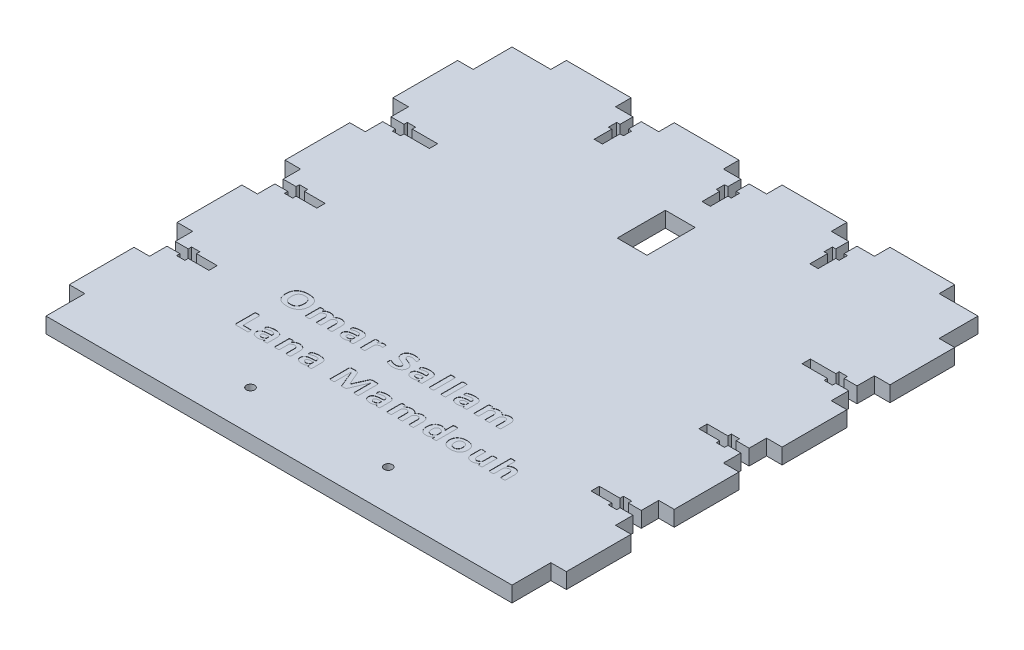
SolidWorks part; units mm, degrees
material "Oak"
ref_plane "Front Plane" through (0, 0, 0) normal (0, 0, 1) x (1, 0, 0)
ref_plane "Top Plane" through (0, 0, 0) normal (0, 1, 0) x (1, 0, 0)
ref_plane "Right Plane" through (0, 0, 0) normal (1, 0, 0) x (0, 0, -1)
sketch "Sketch1" plane through (0, 0, 0) normal (0, 1, 0) x (1, 0, 0)
  line L0 (0, -90) -> (0, 90) construction
  line L2 (90, 43.2667) -> (85, 43.2667)
  line L3 (90, 43.2667) -> (90, 40.0667)
  line L4 (90, 40.0667) -> (85, 40.0667)
  line L5 (72, 43.2667) -> (72, 40.0667)
  line L6 (81.8, 40.0667) -> (72, 40.0667)
  line L7 (81.8, 44.5667) -> (85, 44.5667)
  line L8 (81.8, 44.5667) -> (81.8, 43.2667)
  line L9 (81.8, 38.7667) -> (85, 38.7667)
  line L10 (85, 44.5667) -> (85, 43.2667)
  line L11 (81.8, 40.0667) -> (81.8, 38.7667)
  line L12 (81.8, 43.2667) -> (72, 43.2667)
  line L13 (85, 40.0667) -> (85, 38.7667)
  line L14 (90, 43.2667) -> (90, 50) construction
  line L15 (90, 40.0667) -> (90, 33.3333) construction
  line L16 (-85, 40.0667) -> (-85, 38.7667)
  line L17 (-81.8, 43.2667) -> (-72, 43.2667)
  line L18 (-81.8, 40.0667) -> (-81.8, 38.7667)
  line L19 (-85, 44.5667) -> (-85, 43.2667)
  line L20 (-81.8, 38.7667) -> (-85, 38.7667)
  line L21 (-81.8, 44.5667) -> (-81.8, 43.2667)
  line L22 (-81.8, 44.5667) -> (-85, 44.5667)
  line L23 (-81.8, 40.0667) -> (-72, 40.0667)
  line L24 (-72, 43.2667) -> (-72, 40.0667)
  line L25 (-90, 40.0667) -> (-85, 40.0667)
  line L26 (-90, 43.2667) -> (-90, 40.0667)
  line L27 (-90, 43.2667) -> (-85, 43.2667)
  line L34 (-5.75, 65) -> (5.75, 65)
  line L42 (-5.75, 65) -> (-5.75, 46.4)
  line L52 (-5.75, 46.4) -> (5.75, 46.4)
  line L53 (5.75, 65) -> (5.75, 46.4)
  circle A1 centre (26.6, -74.4) radius 1.6
  circle A2 centre (-26.6, -74.4) radius 1.6
  point P33 (0, 46.4)
  point P38 (25, -74.4)
  point P39 (26.6, -76)
  line B0 (90, 90) -> (75, 90)
  line B1 (75, 90) -> (75, 96)
  line B2 (75, 96) -> (50, 96)
  line B3 (50, 96) -> (50, 90)
  line B4 (50, 90) -> (43.2667, 90)
  line B5 (43.2667, 90) -> (43.2667, 85)
  line B6 (43.2667, 85) -> (44.5667, 85)
  line B7 (44.5667, 85) -> (44.5667, 81.8)
  line B8 (44.5667, 81.8) -> (43.2667, 81.8)
  line B9 (43.2667, 81.8) -> (43.2667, 75)
  line B10 (43.2667, 75) -> (40.0667, 75)
  line B11 (40.0667, 75) -> (40.0667, 81.8)
  line B12 (40.0667, 81.8) -> (38.7667, 81.8)
  line B13 (38.7667, 81.8) -> (38.7667, 85)
  line B14 (38.7667, 85) -> (40.0667, 85)
  line B15 (40.0667, 85) -> (40.0667, 90)
  line B16 (40.0667, 90) -> (33.3333, 90)
  line B17 (33.3333, 90) -> (33.3333, 96)
  line B18 (33.3333, 96) -> (8.3333, 96)
  line B19 (8.3333, 96) -> (8.3333, 90)
  line B20 (8.3333, 90) -> (1.6, 90)
  line B21 (1.6, 90) -> (1.6, 85)
  line B22 (1.6, 85) -> (2.9, 85)
  line B23 (2.9, 85) -> (2.9, 81.8)
  line B24 (2.9, 81.8) -> (1.6, 81.8)
  line B25 (1.6, 81.8) -> (1.6, 75)
  line B26 (1.6, 75) -> (-1.6, 75)
  line B27 (-1.6, 75) -> (-1.6, 81.8)
  line B28 (-1.6, 81.8) -> (-2.9, 81.8)
  line B29 (-2.9, 81.8) -> (-2.9, 85)
  line B30 (-2.9, 85) -> (-1.6, 85)
  line B31 (-1.6, 85) -> (-1.6, 90)
  line B32 (-1.6, 90) -> (-8.3333, 90)
  line B33 (-8.3333, 90) -> (-8.3333, 96)
  line B34 (-8.3333, 96) -> (-33.3333, 96)
  line B35 (-33.3333, 96) -> (-33.3333, 90)
  line B36 (-33.3333, 90) -> (-40.0667, 90)
  line B37 (-40.0667, 90) -> (-40.0667, 85)
  line B38 (-40.0667, 85) -> (-38.7667, 85)
  line B39 (-38.7667, 85) -> (-38.7667, 81.8)
  line B40 (-38.7667, 81.8) -> (-40.0667, 81.8)
  line B41 (-40.0667, 81.8) -> (-40.0667, 75)
  line B42 (-40.0667, 75) -> (-43.2667, 75)
  line B43 (-43.2667, 75) -> (-43.2667, 81.8)
  line B44 (-43.2667, 81.8) -> (-44.5667, 81.8)
  line B45 (-44.5667, 81.8) -> (-44.5667, 85)
  line B46 (-44.5667, 85) -> (-43.2667, 85)
  line B47 (-43.2667, 85) -> (-43.2667, 90)
  line B48 (-43.2667, 90) -> (-50, 90)
  line B49 (-50, 90) -> (-50, 96)
  line B50 (-50, 96) -> (-75, 96)
  line B51 (-75, 96) -> (-75, 90)
  line B52 (-75, 90) -> (-90, 90)
  line B53 (-90, 90) -> (-90, 75)
  line B54 (-90, 75) -> (-96, 75)
  line B55 (-96, 75) -> (-96, 50)
  line B56 (-96, 50) -> (-90, 50)
  line B57 (-90, 50) -> (-90, 33.3333)
  line B58 (-90, 33.3333) -> (-96, 33.3333)
  line B59 (-96, 33.3333) -> (-96, 8.3333)
  line B60 (-96, 8.3333) -> (-90, 8.3333)
  line B61 (-90, 8.3333) -> (-90, 1.6)
  line B62 (-90, 1.6) -> (-85, 1.6)
  line B63 (-85, 1.6) -> (-85, 2.9)
  line B64 (-85, 2.9) -> (-81.8, 2.9)
  line B65 (-81.8, 2.9) -> (-81.8, 1.6)
  line B66 (-81.8, 1.6) -> (-73.8, 1.6)
  line B67 (-73.8, 1.6) -> (-73.8, -1.6)
  line B68 (-73.8, -1.6) -> (-81.8, -1.6)
  line B69 (-81.8, -1.6) -> (-81.8, -2.9)
  line B70 (-81.8, -2.9) -> (-85, -2.9)
  line B71 (-85, -2.9) -> (-85, -1.6)
  line B72 (-85, -1.6) -> (-90, -1.6)
  line B73 (-90, -1.6) -> (-90, -8.3333)
  line B74 (-90, -8.3333) -> (-96, -8.3333)
  line B75 (-96, -8.3333) -> (-96, -33.3333)
  line B76 (-96, -33.3333) -> (-90, -33.3333)
  line B77 (-90, -33.3333) -> (-90, -40.0667)
  line B78 (-90, -40.0667) -> (-85, -40.0667)
  line B79 (-85, -40.0667) -> (-85, -38.7667)
  line B80 (-85, -38.7667) -> (-81.8, -38.7667)
  line B81 (-81.8, -38.7667) -> (-81.8, -40.0667)
  line B82 (-81.8, -40.0667) -> (-73.8, -40.0667)
  line B83 (-73.8, -40.0667) -> (-73.8, -43.2667)
  line B84 (-73.8, -43.2667) -> (-81.8, -43.2667)
  line B85 (-81.8, -43.2667) -> (-81.8, -44.5667)
  line B86 (-81.8, -44.5667) -> (-85, -44.5667)
  line B87 (-85, -44.5667) -> (-85, -43.2667)
  line B88 (-85, -43.2667) -> (-90, -43.2667)
  line B89 (-90, -43.2667) -> (-90, -50)
  line B90 (-90, -50) -> (-96, -50)
  line B91 (-96, -50) -> (-96, -75)
  line B92 (-96, -75) -> (-90, -75)
  line B93 (-90, -75) -> (-90, -90)
  line B94 (-90, -90) -> (90, -90)
  line B95 (90, -90) -> (90, -75)
  line B96 (90, -75) -> (96, -75)
  line B97 (96, -75) -> (96, -50)
  line B98 (96, -50) -> (90, -50)
  line B99 (90, -50) -> (90, -43.2667)
  line B100 (90, -43.2667) -> (85, -43.2667)
  line B101 (85, -43.2667) -> (85, -44.5667)
  line B102 (85, -44.5667) -> (81.8, -44.5667)
  line B103 (81.8, -44.5667) -> (81.8, -43.2667)
  line B104 (81.8, -43.2667) -> (73.8, -43.2667)
  line B105 (73.8, -43.2667) -> (73.8, -40.0667)
  line B106 (73.8, -40.0667) -> (81.8, -40.0667)
  line B107 (81.8, -40.0667) -> (81.8, -38.7667)
  line B108 (81.8, -38.7667) -> (85, -38.7667)
  line B109 (85, -38.7667) -> (85, -40.0667)
  line B110 (85, -40.0667) -> (90, -40.0667)
  line B111 (90, -40.0667) -> (90, -33.3333)
  line B112 (90, -33.3333) -> (96, -33.3333)
  line B113 (96, -33.3333) -> (96, -8.3333)
  line B114 (96, -8.3333) -> (90, -8.3333)
  line B115 (90, -8.3333) -> (90, -1.6)
  line B116 (90, -1.6) -> (85, -1.6)
  line B117 (85, -1.6) -> (85, -2.9)
  line B118 (85, -2.9) -> (81.8, -2.9)
  line B119 (81.8, -2.9) -> (81.8, -1.6)
  line B120 (81.8, -1.6) -> (73.8, -1.6)
  line B121 (73.8, -1.6) -> (73.8, 1.6)
  line B122 (73.8, 1.6) -> (81.8, 1.6)
  line B123 (81.8, 1.6) -> (81.8, 2.9)
  line B124 (81.8, 2.9) -> (85, 2.9)
  line B125 (85, 2.9) -> (85, 1.6)
  line B126 (85, 1.6) -> (90, 1.6)
  line B127 (90, 1.6) -> (90, 8.3333)
  line B128 (90, 8.3333) -> (96, 8.3333)
  line B129 (96, 8.3333) -> (96, 33.3333)
  line B130 (96, 33.3333) -> (90, 33.3333)
  line B131 (90, 33.3333) -> (90, 50)
  line B132 (90, 50) -> (96, 50)
  line B133 (96, 50) -> (96, 75)
  line B134 (96, 75) -> (90, 75)
  line B135 (90, 75) -> (90, 90)
  dimension "D9" = 3.2
  dimension "D1" = 3.2
  dimension "D2" = 5.8
  dimension "D3" = 3.2
  dimension "D4" = 18
  dimension "D5" = 5
  dimension "D6" = 18.6
  dimension "D7" = 11.5
  dimension "D8" = 10
  dimension "D11" = 14
  dimension "D10" = 25
sketch_block_instance "MainBody-1"
sketch_block "MainBody"
extrude "Boss-Extrude1" add sketch "Sketch1" along normal blind 6 contours B134 B135 B0 B1 B2 B3 B4 B5 B6 B7 B8 B9 B10 B11 B12 B13 B14 B15 B16 B17 B18 B19 B20 B21 B22 B23 B24 B25 B26 B27 B28 B29 B30 B31 B32 B33 B34 B35 B36 B37 B38 B39 B40 B41 B42 B43 B44 B45 B46 B47 B48
sketch "Sketch2" plane through (0, 6, 0) normal (0, 1, 0) x (1, 0, 0)
  line L1 (-73.8, -40.0667) -> (-73.8, -43.2667) construction
  line L2 (-90, -90) -> (90, -90) construction
  text T0 "Omar Sallam\r\nLana Mamdouh" font "Calibri" height 8
  point P1 (-33.8, -36.9024)
  point P5 (-73.8, -41.6667)
  point P6 (-23.8, -45)
  point P7 (-23.8, -45)
  dimension "D1" = 50
  dimension "D2" = 22
extrude "Cut-Extrude1" cut sketch "Sketch2" against normal blind 0.1
